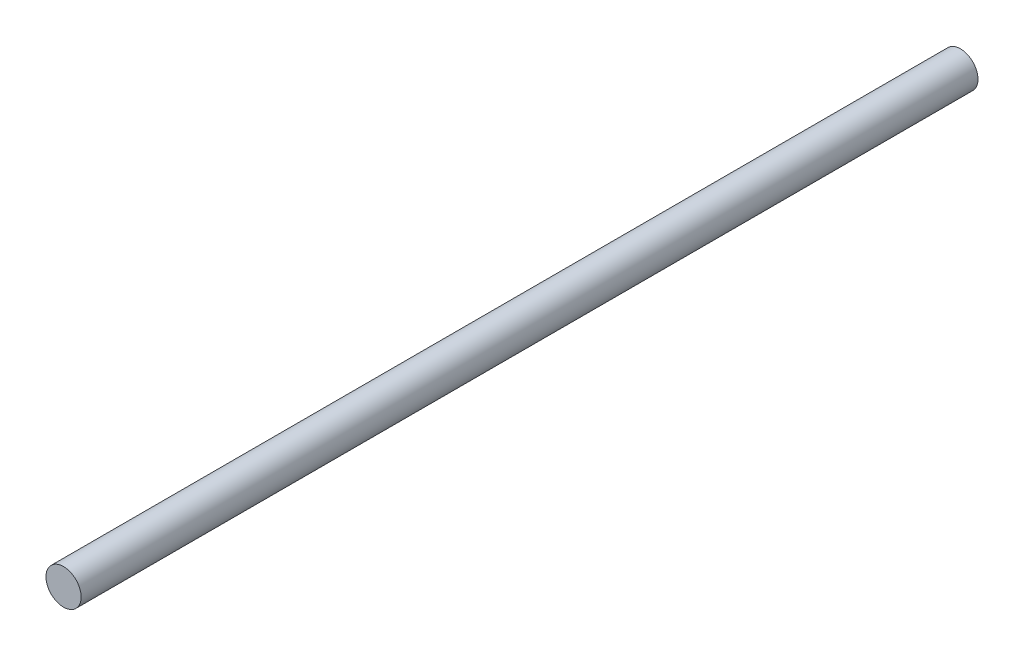
SolidWorks part; units mm, degrees
ref_plane "Front Plane" through (0, 0, 0) normal (0, 0, 1) x (1, 0, 0)
ref_plane "Top Plane" through (0, 0, 0) normal (0, 1, 0) x (1, 0, 0)
ref_plane "Right Plane" through (0, 0, 0) normal (1, 0, 0) x (0, 0, -1)
sketch "Sketch1" plane through (0, 0, 0) normal (0, 0, 1) x (1, 0, 0)
  circle A0 centre (0, 0) radius 5
  dimension "D1" = 10
extrude "Boss-Extrude1" add sketch "Sketch1" along normal blind 255
